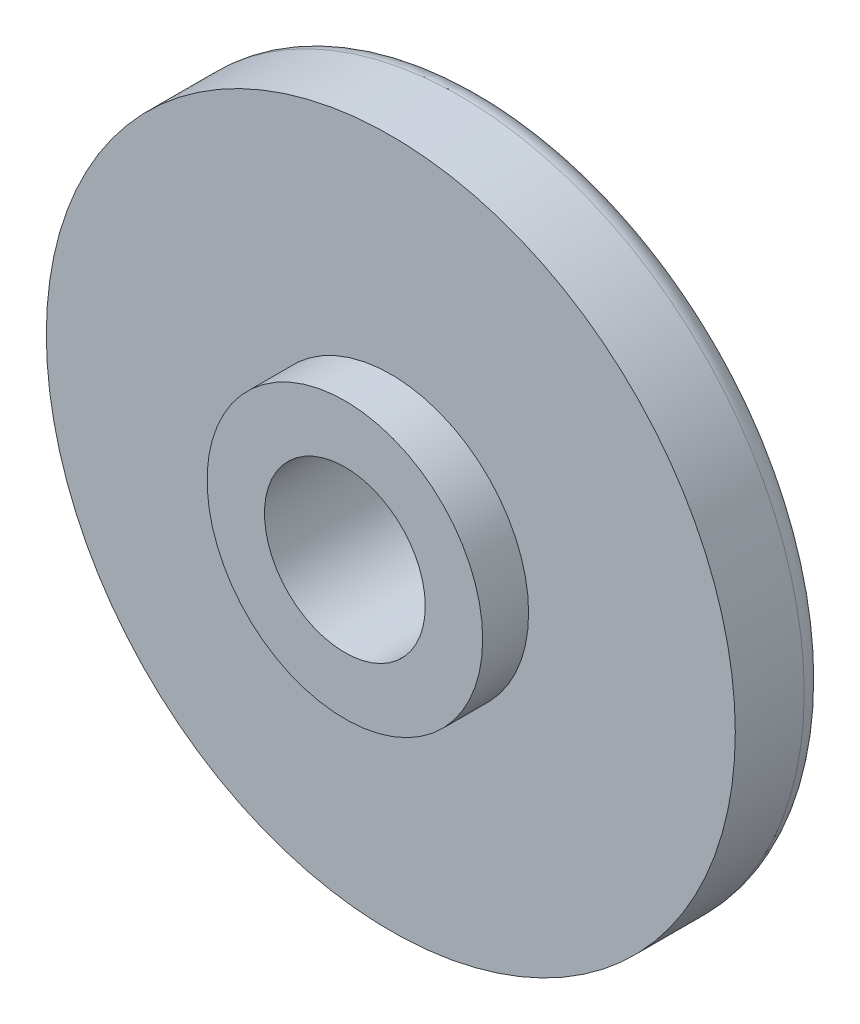
SolidWorks part; units mm, degrees
ref_plane "Front Plane" through (0, 0, 0) normal (0, 0, 1) x (1, 0, 0)
ref_plane "Top Plane" through (0, 0, 0) normal (0, 1, 0) x (1, 0, 0)
ref_plane "Right Plane" through (0, 0, 0) normal (1, 0, 0) x (0, 0, -1)
sketch "Sketch1" plane through (0, 0, 0) normal (0, 0, 1) x (1, 0, 0)
  circle A0 centre (0, 0) radius 1.75
  circle A1 centre (0, 0) radius 7.5
  dimension "D1" = 15
  dimension "D2" = 3.5
extrude "Boss-Extrude1" add sketch "Sketch1" along normal blind 2
sketch "Sketch2" plane through (0, 0, 2) normal (0, 0, 1) x (1, 0, 0)
  circle A1 centre (0, 0) radius 3
  circle A2 centre (0, 0) radius 1.75
  dimension "D1" = 6
  dimension "D2" = 3.5
extrude "Boss-Extrude2" add sketch "Sketch2" along normal blind 1
fillet "Fillet1" radius 0.5 1 edges at (7.5, 0, 0)
